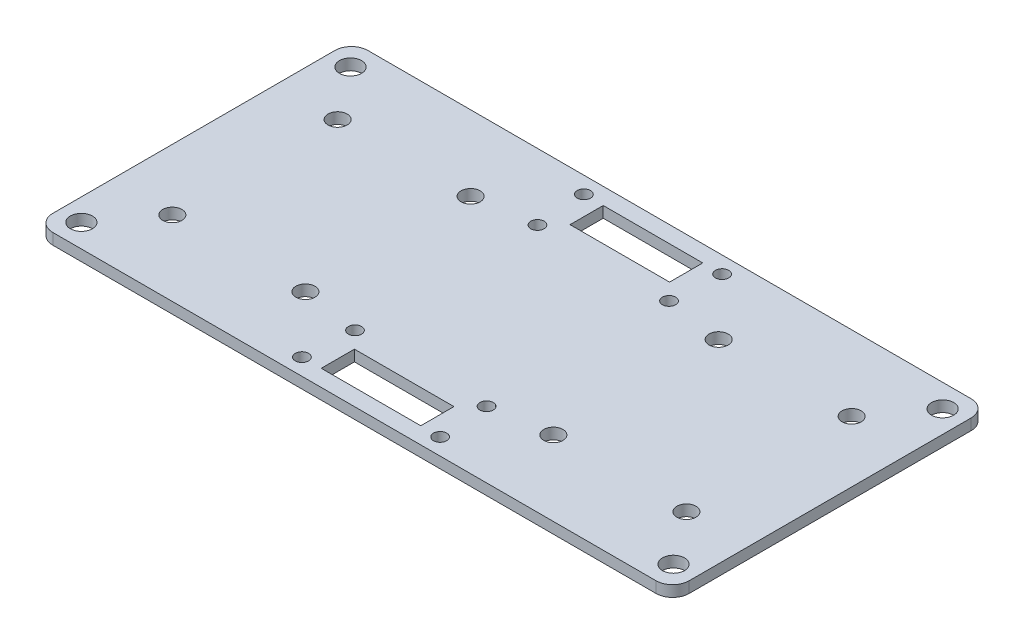
SolidWorks part; units mm, degrees
ref_plane "Plano frontal" through (0, 0, 0) normal (0, 0, 1) x (1, 0, 0)
ref_plane "Plano superior" through (0, 0, 0) normal (0, 1, 0) x (1, 0, 0)
ref_plane "Plano direito" through (0, 0, 0) normal (1, 0, 0) x (0, 0, -1)
sketch "Esboço1" plane through (0, 0, 0) normal (0, 1, 0) x (1, 0, 0)
  line L7 (-57.5484, 29.5) -> (57.5484, 29.5)
  line L8 (57.5484, 29.5) -> (57.5484, -27.5)
  line L9 (57.5484, -27.5) -> (-57.5484, -27.5)
  line L10 (-57.5484, -27.5) -> (-57.5484, 29.5)
  line L11 (0, 29.5) -> (0, -27.5) construction
  line L12 (-57.5484, 1) -> (57.5484, 1) construction
  dimension "D1" = 57
  dimension "D2" = 115.0968
extrude "Ressalto-extrusão1" add sketch "Esboço1" along normal blind 2
sketch "Esboço2" plane through (0, 2, 0) normal (0, 1, 0) x (1, 0, 0)
  line L0 (0, 29.5) -> (0, -27.5) construction
  line L1 (57.5484, 29.5) -> (-57.5484, 29.5) construction
  line L2 (-57.5484, -27.5) -> (57.5484, -27.5) construction
  circle A0 centre (-46.4884, 15.945) radius 1.73
  circle A1 centre (-22.4284, 15.945) radius 1.73
  circle A2 centre (-22.4284, -13.945) radius 1.73
  circle A5 centre (22.4284, -13.945) radius 1.73
  circle A6 centre (22.4284, 15.945) radius 1.73
  circle A7 centre (46.4884, 15.945) radius 1.73
  circle A8 centre (-46.4884, -13.945) radius 1.73
  circle A9 centre (46.4884, -13.945) radius 1.73
extrude "Corte-extrusão1" cut sketch "Esboço2" against normal through all
sketch "Esboço3" plane through (0, 0, 0) normal (0, -1, 0) x (1, 0, 0)
  line L0 (0, 27.5) -> (0, 24.5) construction
  line L1 (-57.5484, 27.5) -> (57.5484, 27.5) construction
  line L2 (-9, 24.5) -> (9, 24.5)
  line L3 (9, 24.5) -> (9, 18.5)
  line L4 (-9, 24.5) -> (-9, 18.5)
  line L5 (-9, 18.5) -> (9, 18.5)
  line L6 (-57.5484, -1) -> (57.5484, -1) construction
  line L7 (-57.5484, -29.5) -> (-57.5484, 27.5) construction
  line L8 (57.5484, 27.5) -> (57.5484, -29.5) construction
  line L9 (9, 24.5) -> (9, 18.5)
  line L10 (-9, 24.5) -> (-9, 18.5)
  line L11 (9, 24.5) -> (9, 18.5)
  line L12 (-9, 24.5) -> (-9, 18.5)
  line L13 (9, 24.5) -> (9, 18.5)
  line L14 (-9, 24.5) -> (-9, 18.5)
  line L15 (0, -29.5) -> (0, -26.5) construction
  line L16 (-9, -26.5) -> (-9, -20.5)
  line L17 (9, -26.5) -> (9, -20.5)
  line L18 (-9, -26.5) -> (-9, -20.5)
  line L19 (9, -26.5) -> (9, -20.5)
  line L20 (-9, -26.5) -> (-9, -20.5)
  line L21 (9, -26.5) -> (9, -20.5)
  line L22 (-9, -20.5) -> (9, -20.5)
  line L23 (-9, -26.5) -> (-9, -20.5)
  line L24 (9, -26.5) -> (9, -20.5)
  line L25 (-9, -26.5) -> (9, -26.5)
  point P8 (0, 24.5)
  point P22 (0, -26.5)
  dimension "D1" = 3
  dimension "D2" = 18
  dimension "D3" = 6
extrude "Corte-extrusão2" cut sketch "Esboço3" against normal through all contours L4 L5 L3 L2 | L16 L25 L17 L22
sketch "Esboço5" plane through (0, 2, 0) normal (0, 1, 0) x (1, 0, 0)
  line L0 (53.5484, 21.175) -> (53.5484, 29.5) construction
  line L1 (19.1984, 21.175) -> (47.5484, 21.175) construction
  line L2 (57.5484, 29.5) -> (-57.5484, 29.5) construction
  line L3 (57.5484, -27.5) -> (57.5484, 29.5) construction
  line L4 (57.5484, 1) -> (-57.5484, 1) construction
  line L5 (-57.5484, 29.5) -> (-57.5484, -27.5) construction
  line L6 (0, 29.5) -> (0, -27.5) construction
  line L7 (-57.5484, -27.5) -> (57.5484, -27.5) construction
  line L8 (53.5484, -19.175) -> (53.5484, -27.5) construction
  line L9 (-53.5484, -19.175) -> (-53.5484, -27.5) construction
  line L10 (-53.5484, 21.175) -> (-53.5484, 29.5) construction
  circle A0 centre (53.5484, 25.3375) radius 2
  circle A1 centre (53.5484, -23.3375) radius 2
  circle A2 centre (-53.5484, -23.3375) radius 2
  circle A3 centre (-53.5484, 25.3375) radius 2
  dimension "D2" = 4
  dimension "D1" = 4
extrude "Corte-extrusão3" cut sketch "Esboço5" against normal through all
fillet "Filete1" radius 3 4 edges at (57.5484, 1, -29.5) (57.5484, 1, 27.5) (-57.5484, 1, 27.5) (-57.5484, 1, -29.5)
sketch "Esboço8" plane through (0, 2, 0) normal (0, 1, 0) x (1, 0, 0)
  line L0 (-57.5484, 26.5) -> (-57.5484, -24.5) construction
  line L1 (54.5484, 29.5) -> (-54.5484, 29.5) construction
  line L2 (0, 0) -> (0, 29.5) construction
  line L3 (57.5484, 1) -> (-57.5484, 1) construction
  line L5 (57.5484, -24.5) -> (57.5484, 26.5) construction
  circle A0 centre (-12.4984, 26.5) radius 1.2
  circle A1 centre (12.4984, 26.5) radius 1.2
  circle A2 centre (12.4984, -24.5) radius 1.2
  circle A3 centre (-12.4984, -24.5) radius 1.2
  circle A4 centre (-11.8984, 17.5) radius 1.2
  circle A5 centre (11.8984, 17.5) radius 1.2
  circle A6 centre (11.8984, -15.5) radius 1.2
  circle A7 centre (-11.8984, -15.5) radius 1.2
  dimension "D1" = 2.4
  dimension "D4" = 2.4
  dimension "D2" = 45.05
  dimension "D3" = 3
  dimension "D5" = 12
  dimension "D6" = 45.65
extrude "Corte-extrusão4" cut sketch "Esboço8" against normal through all
